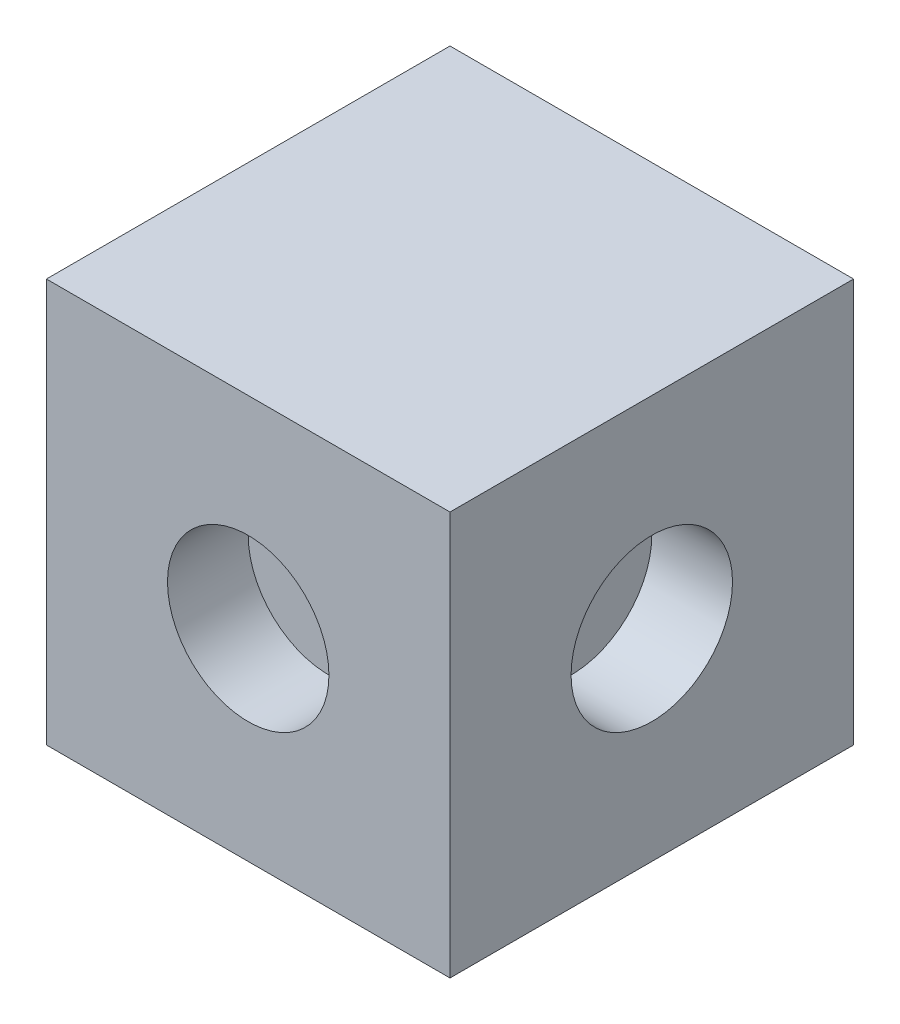
SolidWorks part; units mm, degrees
material "AISI 1020"
ref_plane "Front Plane" through (0, 0, 0) normal (0, 0, 1) x (1, 0, 0)
ref_plane "Top Plane" through (0, 0, 0) normal (0, 1, 0) x (1, 0, 0)
ref_plane "Right Plane" through (0, 0, 0) normal (1, 0, 0) x (0, 0, -1)
sketch "Croquis1" plane through (0, 0, 0) normal (0, 0, 1) x (1, 0, 0)
  line L1 (25, -25) -> (-25, -25)
  line L2 (25, -25) -> (25, 25)
  line L3 (25, 25) -> (-25, 25)
  line L4 (-25, -25) -> (-25, 25)
  line L5 (25, -25) -> (-25, 25) construction
  line L6 (25, 25) -> (-25, -25) construction
  point P0 (0, 0)
  dimension "D1" = 50
extrude "Saliente-Extruir1" add sketch "Croquis1" along normal mid plane 50
sketch "Croquis2" plane through (0, 0, 25) normal (0, 0, 1) x (1, 0, 0)
  circle A0 centre (0, 0) radius 10
  dimension "D1" = 20
extrude "Cortar-Extruir3" cut sketch "Croquis2" against normal blind 10
sketch "Croquis4" plane through (25, 0, 0) normal (1, 0, 0) x (0, 0, -1)
  circle A0 centre (0, 0) radius 10
  dimension "D1" = 20
extrude "Cortar-Extruir4" cut sketch "Croquis4" against normal blind 10
sketch "Croquis5" plane through (0, 0, -25) normal (0, 0, -1) x (-1, 0, 0)
  circle A0 centre (0, 0) radius 10
  dimension "D1" = 20
extrude "Cortar-Extruir5" cut sketch "Croquis5" against normal blind 10
sketch "Croquis6" plane through (-25, 0, 0) normal (-1, 0, 0) x (0, 0, 1)
  circle A0 centre (0, 0) radius 10
  dimension "D1" = 20
extrude "Cortar-Extruir6" cut sketch "Croquis6" against normal blind 10
